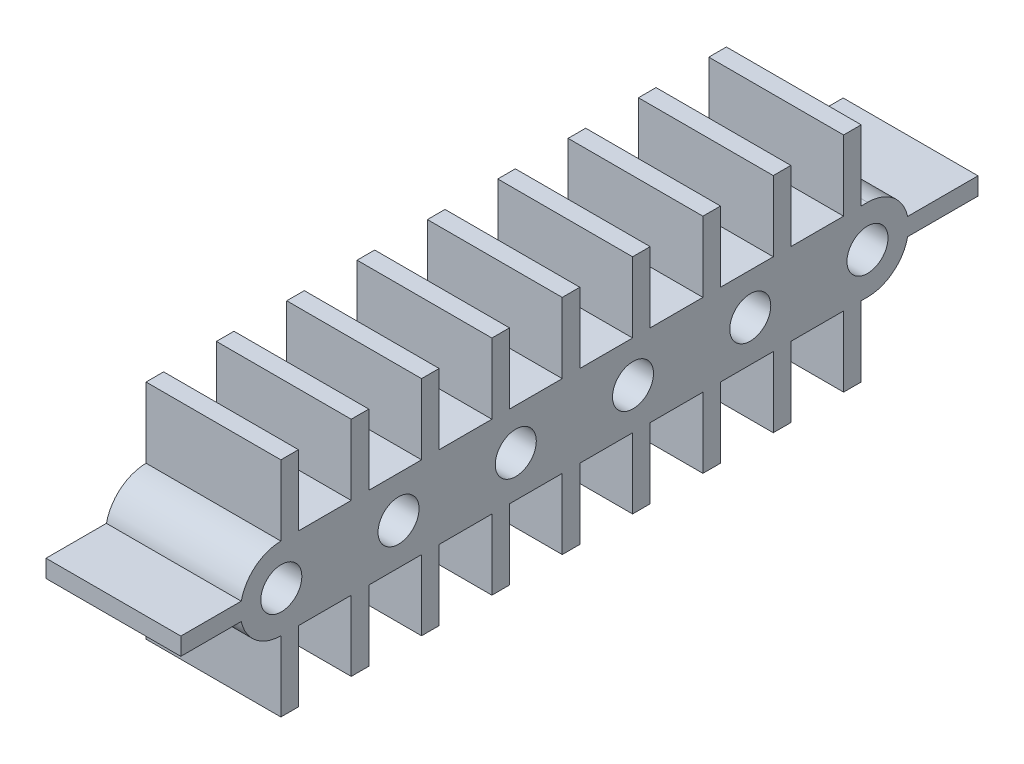
SolidWorks part; units mm, degrees
ref_plane "Front Plane" through (0, 0, 0) normal (0, 0, 1) x (1, 0, 0)
ref_plane "Top Plane" through (0, 0, 0) normal (0, 1, 0) x (1, 0, 0)
ref_plane "Right Plane" through (0, 0, 0) normal (1, 0, 0) x (0, 0, -1)
sketch "Sketch1" plane through (0, 0, 0) normal (1, 0, 0) x (0, 0, -1)
  line L0 (-265.082, 35) -> (-265.082, 95) construction
  line L1 (-250.082, 35) -> (-205.082, 35)
  line L3 (-250.082, -35) -> (-205.082, -35)
  line L5 (-185.082, 35) -> (-145.082, 35)
  line L7 (-265.082, 95) -> (-250.082, 95) construction
  line L8 (-250.082, 95) -> (-250.082, 35) construction
  line L9 (-265.082, 35) -> (-265.082, 95)
  line L10 (-265.082, 95) -> (-250.082, 95)
  line L11 (-250.082, 95) -> (-250.082, 35)
  line L23 (-264.7097, 0) -> (-265.3749, -51.003) construction
  line L27 (-205.082, 35) -> (-205.082, 95)
  line L28 (-205.082, 95) -> (-190.082, 95)
  line L29 (-190.082, 95) -> (-190.082, 35)
  line L30 (-205.082, 35) -> (-205.082, 95) construction
  line L31 (-205.082, 95) -> (-190.082, 95) construction
  line L32 (-190.082, 95) -> (-190.082, 35) construction
  line L33 (-145.082, 35) -> (-145.082, 95)
  line L34 (-145.082, 95) -> (-130.082, 95)
  line L35 (-130.082, 95) -> (-130.082, 35)
  line L36 (-145.082, 35) -> (-145.082, 95) construction
  line L37 (-145.082, 95) -> (-130.082, 95) construction
  line L38 (-130.082, 95) -> (-130.082, 35) construction
  line L39 (-85.082, 35) -> (-85.082, 95)
  line L40 (-85.082, 95) -> (-70.082, 95)
  line L41 (-70.082, 95) -> (-70.082, 35)
  line L42 (-85.082, 35) -> (-85.082, 95) construction
  line L43 (-85.082, 95) -> (-70.082, 95) construction
  line L44 (-70.082, 95) -> (-70.082, 35) construction
  line L45 (-25.082, 35) -> (-25.082, 95)
  line L46 (-25.082, 95) -> (-10.082, 95)
  line L47 (-10.082, 95) -> (-10.082, 35)
  line L48 (-25.082, 35) -> (-25.082, 95) construction
  line L49 (-25.082, 95) -> (-10.082, 95) construction
  line L50 (-10.082, 95) -> (-10.082, 35) construction
  line L51 (34.918, 35) -> (34.918, 95)
  line L52 (34.918, 95) -> (49.918, 95)
  line L53 (49.918, 95) -> (49.918, 35)
  line L54 (34.918, 35) -> (34.918, 95) construction
  line L55 (34.918, 95) -> (49.918, 95) construction
  line L56 (49.918, 95) -> (49.918, 35) construction
  line L57 (94.918, 35) -> (94.918, 95)
  line L58 (94.918, 95) -> (109.918, 95)
  line L59 (109.918, 95) -> (109.918, 35)
  line L60 (94.918, 35) -> (94.918, 95) construction
  line L61 (94.918, 95) -> (109.918, 95) construction
  line L62 (109.918, 95) -> (109.918, 35) construction
  line L63 (154.918, 35) -> (154.918, 95)
  line L64 (154.918, 95) -> (169.918, 95)
  line L65 (169.918, 95) -> (169.918, 35)
  line L66 (154.918, 35) -> (154.918, 95) construction
  line L67 (154.918, 95) -> (169.918, 95) construction
  line L68 (169.918, 95) -> (169.918, 35) construction
  line L69 (214.918, 35) -> (214.918, 95)
  line L70 (214.918, 95) -> (229.918, 95)
  line L71 (229.918, 95) -> (229.918, 35)
  line L72 (214.918, 35) -> (214.918, 95) construction
  line L73 (214.918, 95) -> (229.918, 95) construction
  line L74 (229.918, 95) -> (229.918, 35) construction
  line L75 (-190.082, 35) -> (-185.082, 35)
  line L76 (-130.082, 35) -> (-85.082, 35)
  line L77 (-70.082, 35) -> (-25.082, 35)
  line L78 (-10.082, 35) -> (34.918, 35)
  line L79 (49.918, 35) -> (94.918, 35)
  line L80 (109.918, 35) -> (154.918, 35)
  line L81 (169.918, 35) -> (214.918, 35)
  line L82 (229.918, 35) -> (235.3745, 35)
  line L83 (-264.7097, 0) -> (235.3745, 0) construction
  line L84 (229.918, -95) -> (229.918, -35) construction
  line L85 (214.918, -95) -> (229.918, -95) construction
  line L86 (214.918, -35) -> (214.918, -95) construction
  line L87 (169.918, -95) -> (169.918, -35) construction
  line L88 (154.918, -95) -> (169.918, -95) construction
  line L89 (154.918, -35) -> (154.918, -95) construction
  line L90 (109.918, -95) -> (109.918, -35) construction
  line L91 (94.918, -95) -> (109.918, -95) construction
  line L92 (94.918, -35) -> (94.918, -95) construction
  line L93 (49.918, -95) -> (49.918, -35) construction
  line L94 (34.918, -95) -> (49.918, -95) construction
  line L95 (34.918, -35) -> (34.918, -95) construction
  line L96 (-10.082, -95) -> (-10.082, -35) construction
  line L97 (-25.082, -95) -> (-10.082, -95) construction
  line L98 (-25.082, -35) -> (-25.082, -95) construction
  line L99 (-70.082, -95) -> (-70.082, -35) construction
  line L100 (-85.082, -95) -> (-70.082, -95) construction
  line L101 (-85.082, -35) -> (-85.082, -95) construction
  line L102 (-130.082, -95) -> (-130.082, -35) construction
  line L103 (-145.082, -95) -> (-130.082, -95) construction
  line L104 (-145.082, -35) -> (-145.082, -95) construction
  line L105 (-190.082, -95) -> (-190.082, -35) construction
  line L106 (-205.082, -95) -> (-190.082, -95) construction
  line L107 (-205.082, -35) -> (-205.082, -95) construction
  line L108 (-250.082, -95) -> (-250.082, -35) construction
  line L109 (-265.082, -95) -> (-250.082, -95) construction
  line L110 (-265.082, -35) -> (-265.082, -95) construction
  line L111 (229.918, -95) -> (229.918, -35)
  line L112 (214.918, -95) -> (229.918, -95)
  line L113 (214.918, -35) -> (214.918, -95)
  line L114 (169.918, -95) -> (169.918, -35)
  line L115 (154.918, -95) -> (169.918, -95)
  line L116 (154.918, -35) -> (154.918, -95)
  line L117 (109.918, -95) -> (109.918, -35)
  line L118 (94.918, -95) -> (109.918, -95)
  line L119 (94.918, -35) -> (94.918, -95)
  line L120 (49.918, -95) -> (49.918, -35)
  line L121 (34.918, -95) -> (49.918, -95)
  line L122 (34.918, -35) -> (34.918, -95)
  line L123 (-10.082, -95) -> (-10.082, -35)
  line L124 (-25.082, -95) -> (-10.082, -95)
  line L125 (-25.082, -35) -> (-25.082, -95)
  line L126 (-70.082, -95) -> (-70.082, -35)
  line L127 (-85.082, -95) -> (-70.082, -95)
  line L128 (-85.082, -35) -> (-85.082, -95)
  line L129 (-130.082, -95) -> (-130.082, -35)
  line L130 (-145.082, -95) -> (-130.082, -95)
  line L131 (-145.082, -35) -> (-145.082, -95)
  line L132 (-190.082, -95) -> (-190.082, -35)
  line L133 (-205.082, -95) -> (-190.082, -95)
  line L134 (-205.082, -35) -> (-205.082, -95)
  line L135 (-250.082, -95) -> (-250.082, -35)
  line L136 (-265.082, -95) -> (-250.082, -95)
  line L137 (-265.082, -35) -> (-265.082, -95)
  line L138 (-190.082, -35) -> (-145.082, -35)
  line L139 (-130.082, -35) -> (-85.082, -35)
  line L140 (-70.082, -35) -> (-25.082, -35)
  line L141 (-10.082, -35) -> (34.918, -35)
  line L142 (49.918, -35) -> (94.918, -35)
  line L143 (109.918, -35) -> (154.918, -35)
  line L144 (169.918, -35) -> (214.918, -35)
  line L145 (229.918, -35) -> (235.3745, -35)
  line L146 (0, 0) -> (0, 35) construction
  line L147 (0, 35) -> (0, -35) construction
  line L148 (-264.7097, 0) -> (-299.6285, 0) construction
  line L149 (-299.6285, 0) -> (-350.4285, 0) construction
  line L150 (-350.4285, 0) -> (-350.4285, 7.5) construction
  line L151 (-350.4285, 0) -> (-350.4285, -7.5) construction
  line L152 (-350.4285, 7.5) -> (-350.4285, -7.5)
  line L153 (-350.4285, 7.5) -> (-298.8987, 7.5)
  line L154 (-350.4285, -7.5) -> (-298.8987, -7.5)
  line L157 (329.5615, 0) -> (329.5615, 7.5) construction
  line L158 (329.5615, 0) -> (329.5615, -7.5) construction
  line L159 (329.5615, 7.5) -> (269.5615, 7.5)
  line L160 (329.5615, -7.5) -> (269.5615, -7.5)
  line L161 (329.5615, 7.5) -> (329.5615, -7.5)
  arc A0 (-265.082, 35) -> (-298.8987, 7.5) centre (-264.7097, 0) ccw
  arc A1 (235.3745, -35) -> (269.5615, -7.5) centre (235.3745, 0) ccw
  circle A2 centre (-264.7097, 0) radius 17.5
  circle A3 centre (-164.7097, 0) radius 17.5
  circle A4 centre (-64.7097, 0) radius 17.5
  circle A5 centre (35.2903, 0) radius 17.5
  circle A6 centre (135.2903, 0) radius 17.5
  circle A7 centre (235.2903, 0) radius 17.5
  arc A8 (-298.8987, -7.5) -> (-265.082, -35) centre (-264.7097, 0) ccw
  arc A9 (269.5615, 7.5) -> (235.3745, 35) centre (235.3745, 0) ccw
  point P0 (0, 0)
  dimension "D5" = 35
  dimension "D1" = 70
  dimension "D2" = 60
  dimension "D3" = 15
  dimension "D4" = 6
  dimension "D6" = 51.5298
  dimension "D7" = 7.5
  dimension "D8" = 60
  dimension "D9" = 7.5
extrude "Boss-Extrude1" add sketch "Sketch1" along normal blind 115
